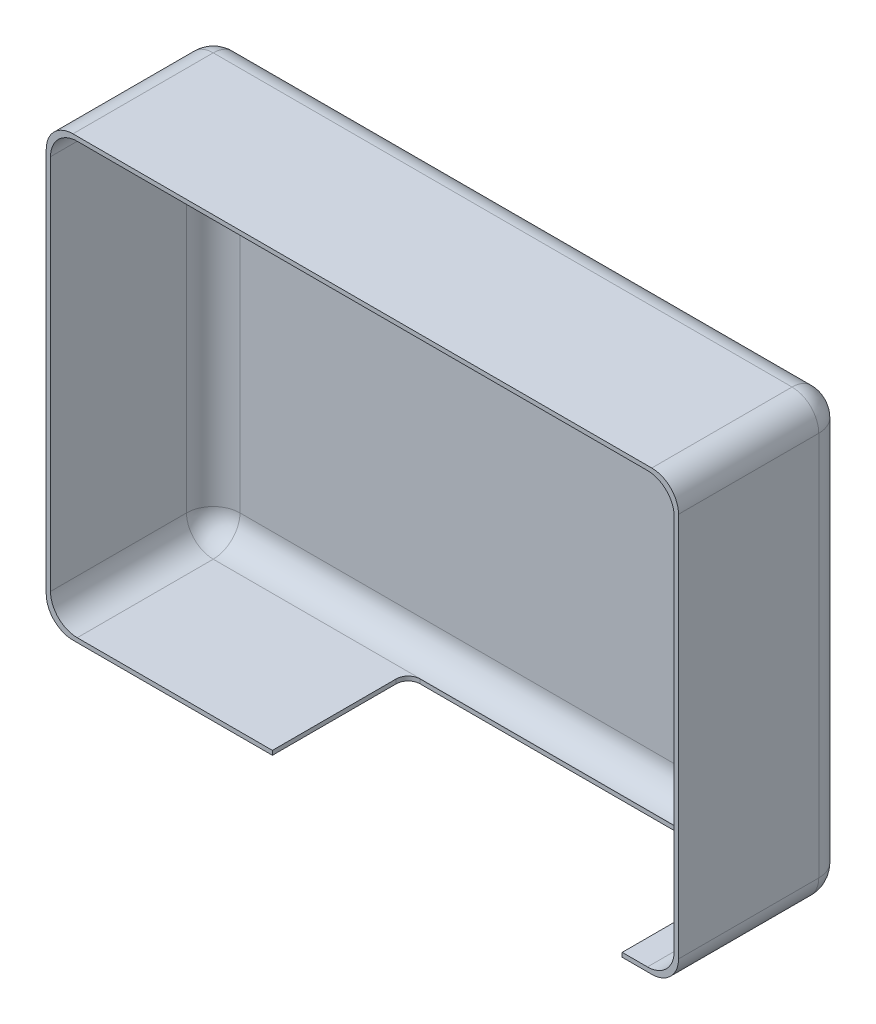
SolidWorks part; units mm, degrees
material "Custom Plastic"
ref_plane "Front Plane" through (0, 0, 0) normal (0, 0, 1) x (1, 0, 0)
ref_plane "Top Plane" through (0, 0, 0) normal (0, 1, 0) x (1, 0, 0)
ref_plane "Right Plane" through (0, 0, 0) normal (1, 0, 0) x (0, 0, -1)
sketch "Sketch1" plane through (0, 0, 0) normal (0, 0, 1) x (1, 0, 0)
  line L1 (-41.4059, 22.0562) -> (266.6961, 22.0562)
  line L2 (-55.6299, 7.8322) -> (-55.6299, -197.1458)
  line L3 (-41.4059, -211.3698) -> (266.6961, -211.3698)
  line L4 (280.9201, 7.8322) -> (280.9201, -197.1458)
  arc A0 (-41.4059, 22.0562) -> (-55.6299, 7.8322) centre (-41.4059, 7.8322) ccw
  arc A1 (-55.6299, -197.1458) -> (-41.4059, -211.3698) centre (-41.4059, -197.1458) ccw
  arc A2 (266.6961, -211.3698) -> (280.9201, -197.1458) centre (266.6961, -197.1458) ccw
  arc A3 (280.9201, 7.8322) -> (266.6961, 22.0562) centre (266.6961, 7.8322) ccw
  point P6 (-55.6299, 22.0562)
  point P9 (-55.6299, -211.3698)
  point P14 (280.9201, 22.0562)
  dimension "D3" = 14.224
  dimension "D4" = 14.224
  dimension "D1" = 336.55
  dimension "D2" = 233.426
extrude "Boss-Extrude1" add sketch "Sketch1" along normal blind 88.9
sketch "Sketch4" plane through (0, 0, 88.9) normal (0, 0, 1) x (1, 0, 0)
  line L0 (-39.1199, -209.0838) -> (264.4101, -209.0838)
  line L1 (-53.3439, -194.8598) -> (-53.3439, 5.5462)
  line L2 (-39.1199, 19.7702) -> (264.4101, 19.7702)
  line L3 (278.6341, -194.8598) -> (278.6341, 5.5462)
  line L4 (266.6961, 22.0562) -> (-41.4059, 22.0562) construction
  line L5 (-55.6299, 7.8322) -> (-55.6299, -197.1458) construction
  arc A0 (-53.3439, -194.8598) -> (-39.1199, -209.0838) centre (-39.1199, -194.8598) ccw
  arc A1 (264.4101, -209.0838) -> (278.6341, -194.8598) centre (264.4101, -194.8598) ccw
  arc A2 (278.6341, 5.5462) -> (264.4101, 19.7702) centre (264.4101, 5.5462) ccw
  arc A3 (-39.1199, 19.7702) -> (-53.3439, 5.5462) centre (-39.1199, 5.5462) ccw
  point P12 (112.6451, 19.7702)
  point P15 (112.6451, 22.0562)
  point P16 (-53.3439, -94.6568)
  point P19 (-55.6299, -94.6568)
extrude "Cut-Extrude1" cut sketch "Sketch4" against normal blind 86.614
fillet "Fillet1" radius 14.224 8 edges at (-49.1778, -204.9177, 2.286) (-53.3439, -94.6568, 2.286) (-49.1778, 15.6041, 2.286) (112.6451, 19.7702, 2.286) (274.4679, 15.6041, 2.286) (278.6341, -94.6568, 2.286) (274.4679, -204.9177, 2.286) (112.6451, -209.0838, 2.286)
fillet "Fillet2" radius 14.224 8 edges at (-55.6299, -94.6568, 0) (-51.4638, 17.8901, 0) (112.6451, 22.0562, 0) (276.7539, 17.8901, 0) (280.9201, -94.6568, 0) (276.7539, -207.2037, 0) (112.6451, -211.3698, 0) (-51.4638, -207.2037, 0)
sketch "Sketch5" plane through (0, -211.3698, 0) normal (0, -1, 0) x (-1, 0, 0)
  line L1 (-64.7582, -88.9) -> (-64.7582, -22.9944)
  line L2 (-71.1082, -16.6444) -> (-244.6158, -16.6444)
  line L3 (-64.7582, -88.9) -> (-250.9658, -88.9)
  line L4 (-250.9658, -22.9944) -> (-250.9658, -88.9)
  arc A0 (-250.9658, -22.9944) -> (-244.6158, -16.6444) centre (-244.6158, -22.9944) cw
  arc A1 (-71.1082, -16.6444) -> (-64.7582, -22.9944) centre (-71.1082, -22.9944) cw
  point P6 (-250.9658, -16.6444)
  point P9 (-64.7582, -16.6444)
  point P12 (-64.7582, -14.224)
  dimension "D1" = 6.35
extrude "Cut-Extrude2" cut sketch "Sketch5" against normal blind 2.286
